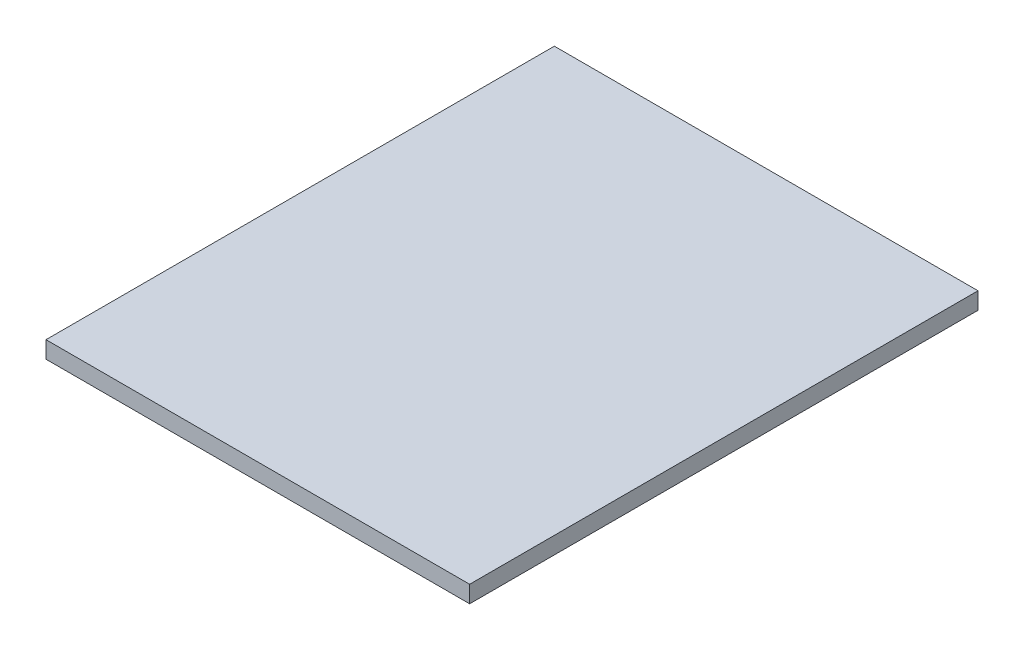
SolidWorks part; units mm, degrees
ref_plane "Front Plane" through (0, 0, 0) normal (0, 0, 1) x (1, 0, 0)
ref_plane "Top Plane" through (0, 0, 0) normal (0, 1, 0) x (1, 0, 0)
ref_plane "Right Plane" through (0, 0, 0) normal (1, 0, 0) x (0, 0, -1)
sketch "Sketch1" plane through (0, 0, 0) normal (0, 1, 0) x (1, 0, 0)
  line L1 (-500, 600) -> (500, 600)
  line L2 (-500, 600) -> (-500, -600)
  line L3 (-500, -600) -> (500, -600)
  line L4 (500, 600) -> (500, -600)
  line L5 (-500, 600) -> (500, -600) construction
  line L6 (-500, -600) -> (500, 600) construction
  point P0 (0, 0)
  dimension "D1" = 1000
  dimension "D2" = 1200
extrude "Boss-Extrude1" add sketch "Sketch1" along normal blind 40
